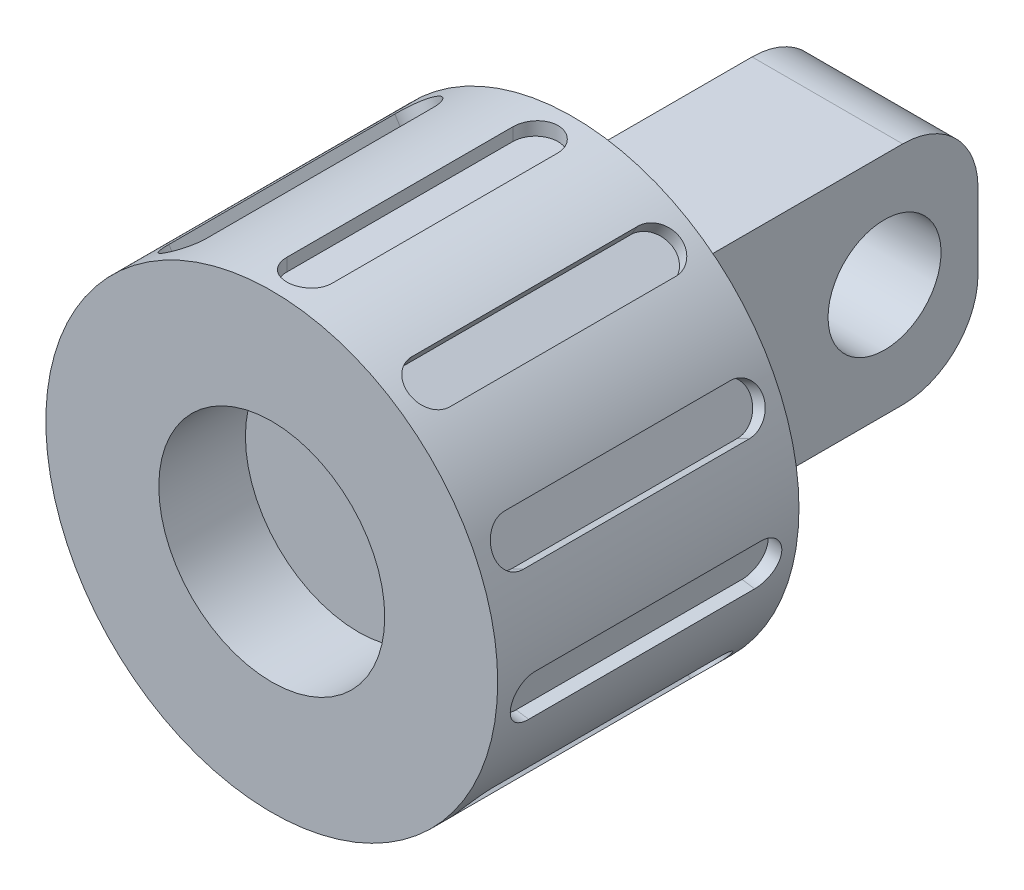
SolidWorks part; units mm, degrees
ref_plane "Ön Düzlem" through (0, 0, 0) normal (0, 0, 1) x (1, 0, 0)
ref_plane "Üst Düzlem" through (0, 0, 0) normal (0, 1, 0) x (1, 0, 0)
ref_plane "Sağ Düzlem" through (0, 0, 0) normal (1, 0, 0) x (0, 0, -1)
sketch "Sketch1" plane through (0, 0, 0) normal (0, 0, 1) x (1, 0, 0)
  circle A0 centre (0, 0) radius 30
  dimension "D1" = 60
extrude "Boss-Extrude1" add sketch "Sketch1" against normal blind 40
sketch "Sketch2" plane through (0, 0, 0) normal (0, 0, 1) x (1, 0, 0)
  circle A0 centre (0, 0) radius 15
  dimension "D1" = 30
extrude "Cut-Extrude1" cut sketch "Sketch2" against normal blind 11.5
sketch "Sketch3" plane through (0, 0, -40) normal (0, 0, -1) x (-1, 0, 0)
  line L1 (10, -15) -> (-10, -15)
  line L2 (10, -15) -> (10, 15)
  line L3 (10, 15) -> (-10, 15)
  line L4 (-10, -15) -> (-10, 15)
  line L5 (10, -15) -> (-10, 15) construction
  line L6 (10, 15) -> (-10, -15) construction
  point P0 (0, 0)
  dimension "D1" = 20
  dimension "D2" = 30
extrude "Boss-Extrude2" add sketch "Sketch3" along normal blind 43.77
fillet "Fillet1" radius 10 2 edges at (0, -15, -83.77) (0, 15, -83.77)
sketch "Sketch4" plane through (-10, 0, 0) normal (-1, 0, 0) x (0, 0, 1)
  line L0 (-40, -15) -> (-40, 15) construction
  circle A0 centre (-71.36, 0) radius 7.5
  dimension "D2" = 15
  dimension "D1" = 31.36
extrude "Cut-Extrude2" cut sketch "Sketch4" against normal blind 43.77
ref_plane "Plane1" through (0, 30, 0) normal (0, 1, 0) x (1, 0, 0)
sketch "Sketch5" plane through (0, 30, 0) normal (0, 1, 0) x (1, 0, 0)
  line L0 (0, 35) -> (0, 5) construction
  line L1 (3, 35) -> (3, 5)
  line L2 (-3, 35) -> (-3, 5)
  line L3 (-30, 0) -> (30, 0) construction
  arc A0 (3, 35) -> (-3, 35) centre (0, 35) ccw
  arc A1 (-3, 5) -> (3, 5) centre (0, 5) ccw
  point P3 (0, 20)
  dimension "D1" = 30
  dimension "D2" = 6
  dimension "D3" = 5
extrude "Cut-Extrude3" cut sketch "Sketch5" against normal blind 1.85
pattern_circular "CirPattern1" count 11 over 360 about axis through (0, 0, 0) along (0, 0, 1) of "Cut-Extrude3"
